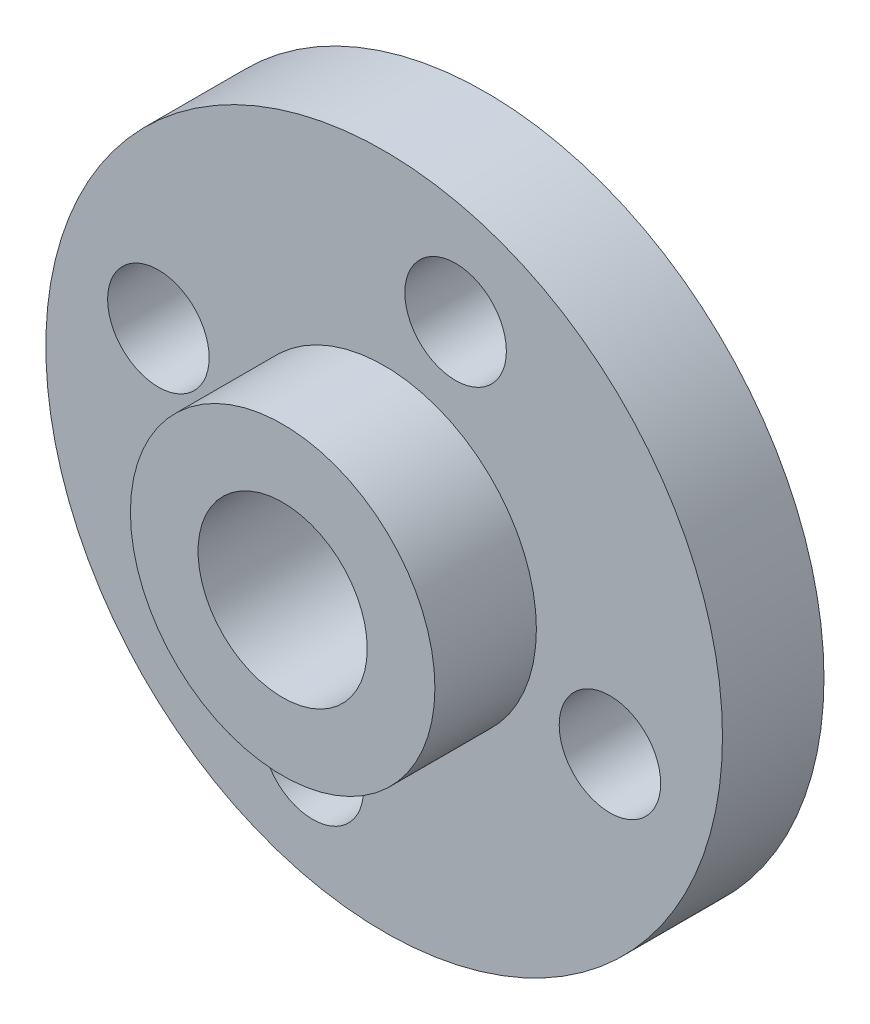
SolidWorks part; units mm, degrees
ref_plane "Front Plane" through (0, 0, 0) normal (0, 0, 1) x (1, 0, 0)
ref_plane "Top Plane" through (0, 0, 0) normal (0, 1, 0) x (1, 0, 0)
ref_plane "Right Plane" through (0, 0, 0) normal (1, 0, 0) x (0, 0, -1)
sketch "Sketch1" plane through (0, 0, 0) normal (0, 0, 1) x (1, 0, 0)
  circle A0 centre (0, 0) radius 10
extrude "Boss-Extrude1" add sketch "Sketch1" along normal blind 3
sketch "Sketch2" plane through (0, 0, 3) normal (0, 0, 1) x (1, 0, 0)
  circle A0 centre (0, 0) radius 4.5
  point P3 (0, 0)
  point P4 (0, 0)
  dimension "D1" = 9
extrude "Boss-Extrude2" add sketch "Sketch2" along normal blind 3
hole_wizard "Ø3.0mm Dowel Hole1" positions "Sketch5" profile "Sketch7" hole size "Ø3.0" standard "ISO" end condition through all
sketch "Sketch5" plane through (0, 0, 0) normal (0, 0, -1) x (-1, 0, 0)
  point P3 (6.6737, 2.1123)
  point P8 (2.1123, -6.6737)
  point P9 (-6.6737, -2.1123)
  point P10 (-2.1123, 6.6737)
  point P15 (0, 0)
  point P16 (0, 0)
  dimension "D2" = 4
sketch "Sketch7" plane through (-6.6737, 2.1123, 0) normal (1, 0, 0) x (0, 1, 0)
  line L0 (0, 0) -> (0, 6)
  line L1 (0, 6) -> (1.5, 6)
  line L2 (1.5, 6) -> (1.5, 0)
  line L5 (1.5, 0) -> (0, 0)
  line L11 (0, -6.35) -> (0, 107.95) construction
  dimension "Thru Hole Dia." = 3
  dimension "Thru Hole Depth" = 6
hole_wizard "Ø5.0mm Dowel Hole1" positions "Sketch8" profile "Sketch9" hole size "Ø5.0" standard "ISO" end condition through all
sketch "Sketch8" plane through (0, 0, 6) normal (0, 0, 1) x (1, 0, 0)
  point P0 (0, 0)
sketch "Sketch9" plane through (0, 0, 6) normal (1, 0, 0) x (0, -1, 0)
  line L0 (0, 0) -> (0, 6)
  line L1 (0, 6) -> (2.5, 6)
  line L2 (2.5, 6) -> (2.5, 0)
  line L5 (2.5, 0) -> (0, 0)
  line L11 (0, -6.35) -> (0, 107.95) construction
  dimension "Thru Hole Dia." = 5
  dimension "Thru Hole Depth" = 6
